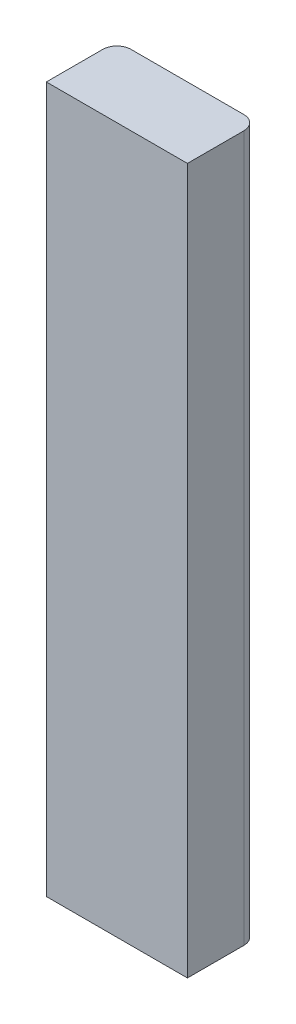
SolidWorks part; units mm, degrees
ref_plane "Front Plane" through (0, 0, 0) normal (0, 0, 1) x (1, 0, 0)
ref_plane "Top Plane" through (0, 0, 0) normal (0, 1, 0) x (1, 0, 0)
ref_plane "Right Plane" through (0, 0, 0) normal (1, 0, 0) x (0, 0, -1)
sketch "Sketch2" plane through (0, 0, 0) normal (0, 1, 0) x (1, 0, 0)
  line L0 (0, 0) -> (0, 12.7)
  line L1 (0, 12.7) -> (25.4, 12.7)
  line L2 (25.4, 12.7) -> (25.4, 0)
  line L3 (25.4, 0) -> (0, 0)
  dimension "D1" = 12.7
  dimension "D2" = 25.4
extrude "Boss-Extrude2" add sketch "Sketch2" along normal blind 127
fillet "Fillet1" radius 2.54 2 edges at (0, 63.5, -12.7) (25.4, 63.5, -12.7)
